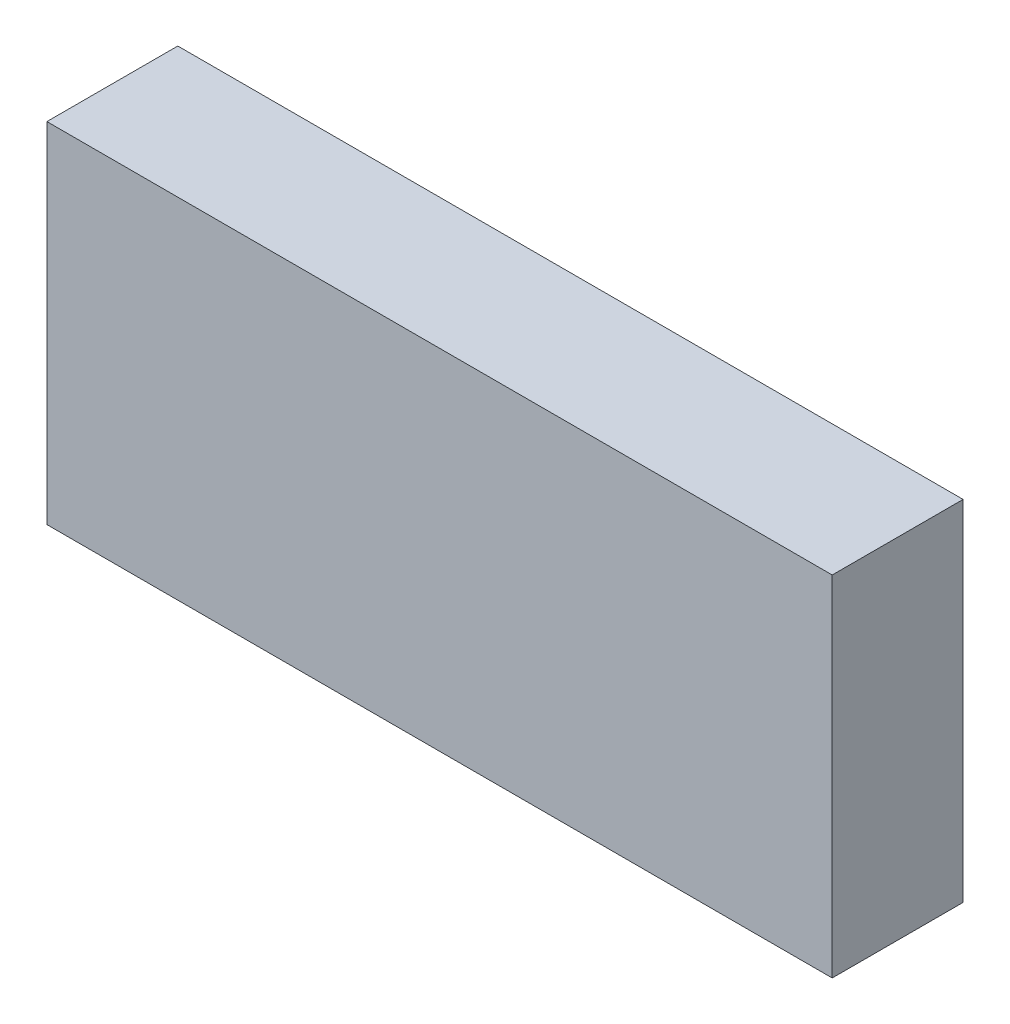
SolidWorks part; units mm, degrees
material "Cobalt"
ref_plane "Front Plane" through (0, 0, 0) normal (0, 0, 1) x (1, 0, 0)
ref_plane "Top Plane" through (0, 0, 0) normal (0, 1, 0) x (1, 0, 0)
ref_plane "Right Plane" through (0, 0, 0) normal (1, 0, 0) x (0, 0, -1)
sketch "Sketch1" plane through (0, 0, 0) normal (0, 0, 1) x (1, 0, 0)
  line L1 (0, 0) -> (900, 0)
  line L2 (0, 0) -> (0, 400)
  line L3 (0, 400) -> (900, 400)
  line L4 (900, 0) -> (900, 400)
  dimension "D1" = 900
  dimension "D2" = 400
extrude "Boss-Extrude1" add sketch "Sketch1" along normal blind 150
